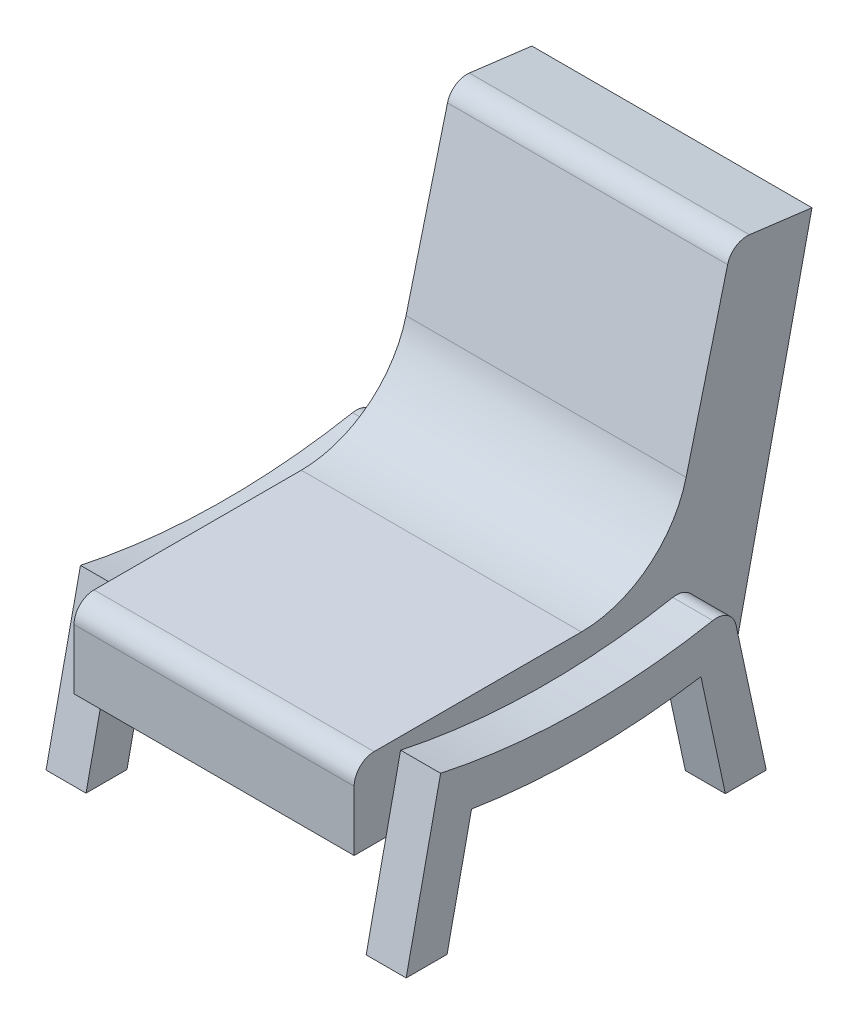
SolidWorks part; units mm, degrees
ref_plane "Front Plane" through (0, 0, 0) normal (0, 0, 1) x (1, 0, 0)
ref_plane "Top Plane" through (0, 0, 0) normal (0, 1, 0) x (1, 0, 0)
ref_plane "Right Plane" through (0, 0, 0) normal (1, 0, 0) x (0, 0, -1)
sketch "Sketch1" plane through (0, 0, 0) normal (1, 0, 0) x (0, 0, -1)
  line L0 (-45, 0) -> (45, 0) construction
  line L1 (-45, 0) -> (-36.3929, 40)
  line L2 (36.3929, 40) -> (45, 0)
  line L3 (-36.3929, 40) -> (36.3929, 40) construction
  line L4 (-34.7711, 0) -> (-28.6627, 28.3874)
  line L5 (28.6627, 28.3874) -> (34.7711, 0)
  line L6 (45, 0) -> (34.7711, 0)
  line L7 (-45, 0) -> (-34.7711, 0)
  line L8 (-35.2238, -2.1036) -> (-28.6627, 28.3874) construction
  line L9 (28.6627, 28.3874) -> (35.2238, -2.1036) construction
  arc A0 (-36.3929, 40) -> (36.3929, 40) centre (0, 209.1288) ccw
  arc A1 (-28.6627, 28.3874) -> (28.6627, 28.3874) centre (0, 209.1288) ccw
  point P6 (0, 36.1288)
  dimension "D2" = 173
  dimension "D5" = 183
  dimension "D1" = 90
  dimension "D3" = 40
  dimension "D4" = 102.144
extrude "Boss-Extrude1" add sketch "Sketch1" along normal blind 10
fillet "Fillet1" radius 5 1 edges at (5, 40, -36.3929)
ref_plane "Plane1" through (45, 0, 0) normal (1, 0, 0) x (0, 0, -1)
mirror "Mirror3" about plane through (45, 0, 0) normal (1, 0, 0) of bodies 101
sketch "Sketch2" plane through (45, 0, 0) normal (1, 0, 0) x (0, 0, -1)
  line L0 (-48, 23) -> (48, 23)
  line L1 (34.7711, 0) -> (45, 0) construction
  line L2 (44.8959, 102.5181) -> (45.9671, 106.7417)
  line L3 (45, 0) -> (45, -8.4245) construction
  line L4 (-48, 23) -> (-48, 38)
  line L5 (-43, 43) -> (8.7937, 43)
  line L6 (34.965, 63.3623) -> (45.9671, 106.7417)
  line L8 (66.4169, 106) -> (48, 23)
  line L9 (45.9671, 106.7417) -> (46.4169, 108.5154)
  line L10 (46.4169, 108.5154) -> (66.4169, 106)
  arc A0 (8.7937, 43) -> (34.965, 63.3623) centre (8.7937, 70) ccw
  arc A1 (-48, 38) -> (-43, 43) centre (-43, 38) cw
  point P2 (0, 23)
  point P18 (-48, 43)
  dimension "D6" = 5
  dimension "D7" = 27
  dimension "D1" = 23
  dimension "D2" = 3
  dimension "D3" = 83
  dimension "D4" = 20
  dimension "D5" = 20
extrude "Boss-Extrude2" add sketch "Sketch2" along normal mid plane 70 contours L9 L10 L8 L0 L4 A1 L5 A0 L6
fillet "Fillet2" radius 5 1 edges at (45, 108.5154, -46.4169)
